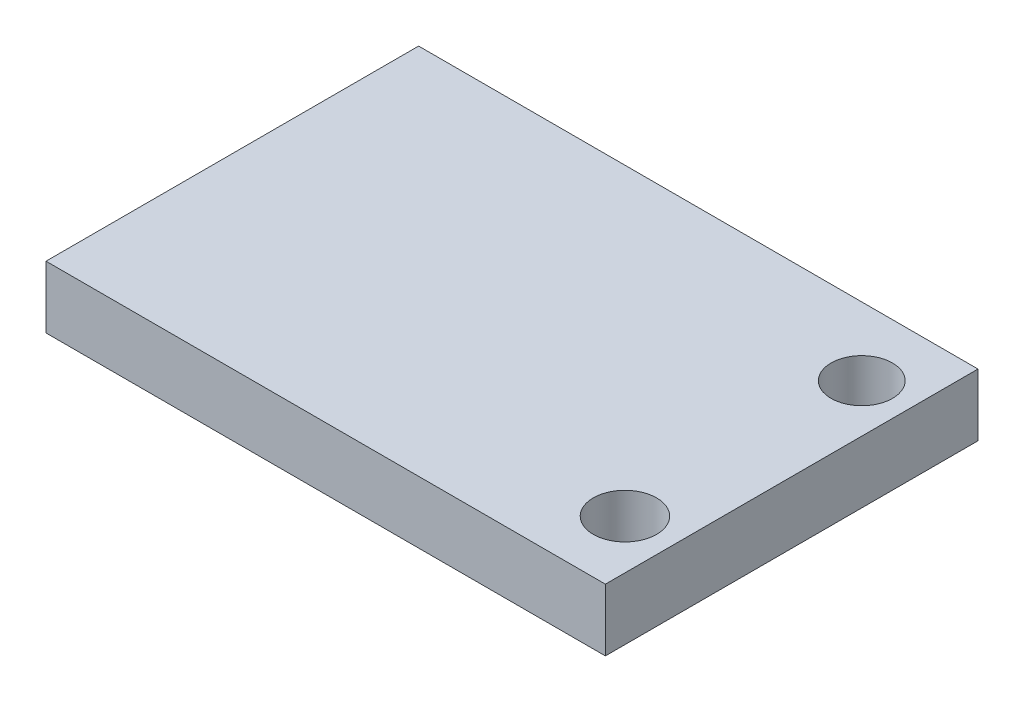
SolidWorks part; units mm, degrees
ref_plane "Front Plane" through (0, 0, 0) normal (0, 0, 1) x (1, 0, 0)
ref_plane "Top Plane" through (0, 0, 0) normal (0, 1, 0) x (1, 0, 0)
ref_plane "Right Plane" through (0, 0, 0) normal (1, 0, 0) x (0, 0, -1)
sketch "Sketch1" plane through (0, 0, 0) normal (0, 1, 0) x (1, 0, 0)
  line L1 (0, 0) -> (-114.261, 0)
  line L2 (0, 0) -> (0, 76.1093)
  line L3 (0, 76.1093) -> (-114.261, 76.1093)
  line L4 (-114.261, 0) -> (-114.261, 76.1093)
extrude "Boss-Extrude1" add sketch "Sketch1" against normal blind 12.7 contours L2 L1 L4 L3
sketch "Sketch2" plane through (0, -12.7, 0) normal (0, -1, 0) x (1, 0, 0)
  line L0 (0, -38.0546) -> (-114.261, -38.0546)
  line L1 (0, 0) -> (0, -76.1093) construction
  line L2 (-114.261, 0) -> (-114.261, -76.1093) construction
  line L3 (-57.1305, 0) -> (-57.1305, -76.1093)
  line L4 (0, 0) -> (-114.261, 0) construction
  line L5 (0, -76.1093) -> (-114.261, -76.1093) construction
  circle A0 centre (-10.0357, -14.0297) radius 6.4654
  circle A1 centre (-10.0357, -62.0796) radius 6.3185
  circle A2 centre (-104.2254, -14.0297) radius 6.3185
  circle A3 centre (-104.2254, -62.0796) radius 6.4654
  point P14 (0, 0)
  point P18 (0, 0)
extrude "Cut-Extrude1" cut sketch "Sketch2" against normal blind 28.194 contours A0
sketch "Sketch3" plane through (0, -12.7, 0) normal (0, -1, 0) x (1, 0, 0)
  line L0 (-9.8084, -76.1093) -> (-9.8084, -62.1763)
  line L1 (0, -76.1093) -> (-114.261, -76.1093) construction
  circle A1 centre (-9.8084, -62.1763) radius 6.2728
extrude "Cut-Extrude2" cut sketch "Sketch3" against normal blind 31.242 contours A1
